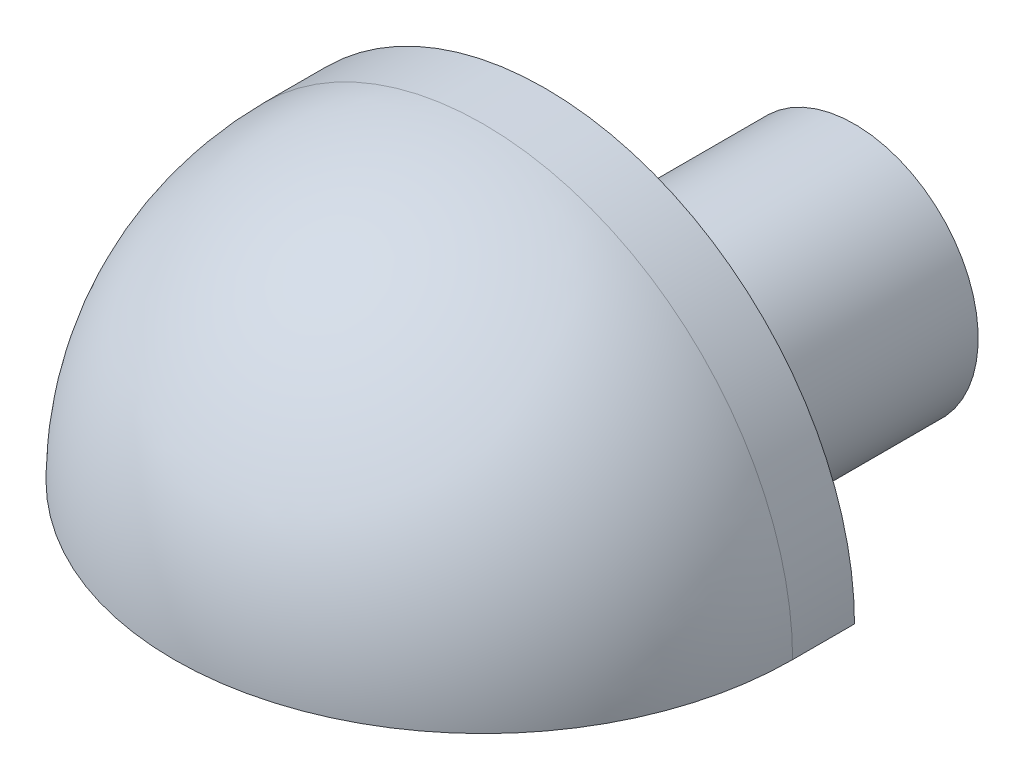
SolidWorks part; units mm, degrees
ref_plane "Alzado" through (0, 0, 0) normal (0, 0, 1) x (1, 0, 0)
ref_plane "Planta" through (0, 0, 0) normal (0, 1, 0) x (1, 0, 0)
ref_plane "Vista lateral" through (0, 0, 0) normal (1, 0, 0) x (0, 0, -1)
sketch "Croquis1" plane through (0, 0, 0) normal (0, 0, 1) x (1, 0, 0)
  line L0 (-80.7873, 3.646) -> (-50.7873, 3.646)
  arc A0 (-80.7873, 3.646) -> (-50.7873, 3.646) centre (-65.7873, 3.646) cw
  dimension "D1" = 30
extrude "Saliente-Extruir1" add sketch "Croquis1" along normal blind 3
sketch "Croquis2" plane through (0, 3.646, 0) normal (0, -1, 0) x (1, 0, 0)
  line L0 (-65.7873, 3) -> (-65.7873, 18) construction
  line L1 (-80.7873, 3) -> (-50.7873, 3) construction
  line L2 (-65.7873, 18) -> (-65.7873, 16.2)
  line L3 (-80.7873, 3) -> (-78.9873, 3)
  arc A0 (-80.7873, 3) -> (-65.7873, 18) centre (-65.7873, 3) cw
  arc A1 (-78.9873, 3) -> (-65.7873, 16.2) centre (-65.7873, 3) cw
  dimension "D1" = 15
  dimension "D2" = 1.8
  dimension "D3" = 1.8
revolve "Revolución1" add sketch "Croquis2" angle 180 about L0
sketch "Croquis3" plane through (0, 0, 0) normal (0, 0, -1) x (-1, 0, 0)
  line L0 (65.7873, 3.646) -> (71.7873, 3.646)
  line L1 (80.7873, 3.646) -> (50.7873, 3.646) construction
  line L2 (65.7873, 3.646) -> (59.7873, 3.646)
  arc A0 (71.7873, 3.646) -> (59.7873, 3.646) centre (65.7873, 3.646) cw
  dimension "D1" = 6
  dimension "D2" = 6
extrude "Saliente-Extruir2" add sketch "Croquis3" against normal up to vertex (3 mm away)
sketch "Croquis4" plane through (0, 0, 0) normal (0, 0, -1) x (-1, 0, 0)
  circle A0 centre (65.7873, 3.646) radius 1.6
extrude "Cortar-Extruir1" cut sketch "Croquis4" against normal blind 3
sketch "Croquis5" plane through (0, 0, 0) normal (0, 0, -1) x (-1, 0, 0)
  circle A0 centre (65.7873, 3.646) radius 1.6
  circle A1 centre (65.7873, 3.646) radius 6
extrude "Saliente-Extruir3" add sketch "Croquis5" along normal blind 15
